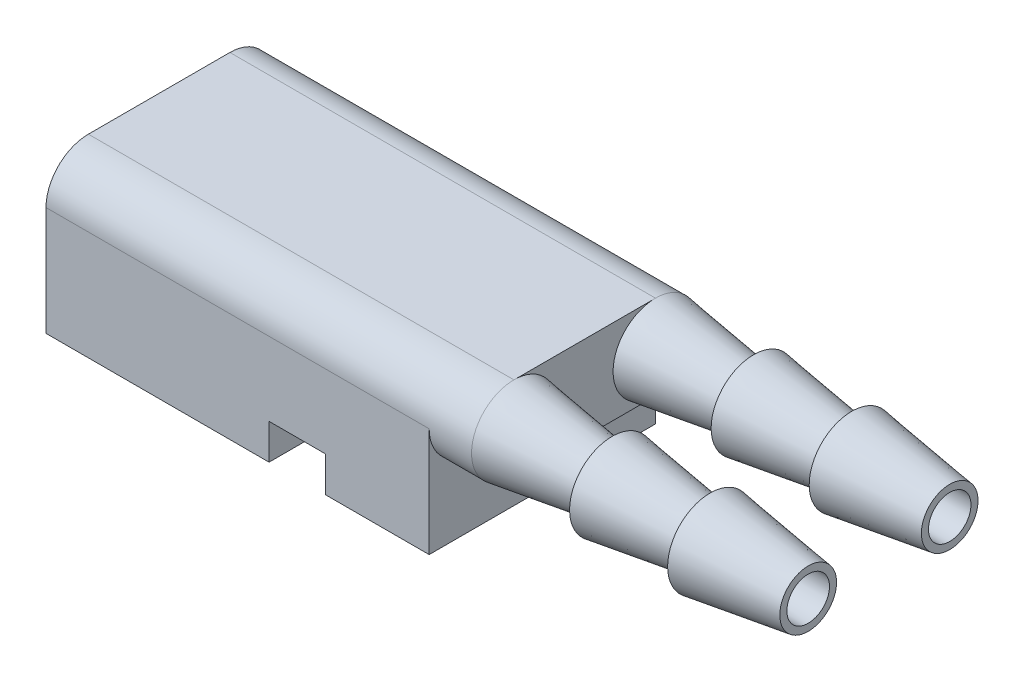
SolidWorks part; units mm, degrees
material "ABS"
ref_plane "Front Plane" through (0, 0, 0) normal (0, 0, 1) x (1, 0, 0)
ref_plane "Top Plane" through (0, 0, 0) normal (0, 1, 0) x (1, 0, 0)
ref_plane "Right Plane" through (0, 0, 0) normal (1, 0, 0) x (0, 0, -1)
sketch "Sketch1" plane through (0, 0, 0) normal (0, 1, 0) x (1, 0, 0)
  line L0 (0, 0) -> (95.5633, 0)
  line L1 (0, 3) -> (0, 1.5016)
  line L2 (0, 1.5016) -> (20.7853, 1.5016)
  line L3 (0, 3) -> (6.5856, 2.051)
  line L4 (6.9284, 2.3479) -> (6.9284, 3)
  line L5 (6.9284, 3) -> (13.5141, 2.051)
  line L6 (13.8569, 2.3479) -> (13.8569, 3)
  line L7 (13.8569, 3) -> (20.7853, 2.0016)
  line L8 (20.7853, 2.0016) -> (20.7853, 1.5016)
  line L9 (0, -8.4984) -> (20.7853, -8.4984)
  line L10 (0, -10) -> (26.2644, -10)
  line L11 (0, -7) -> (0, -8.4984)
  line L12 (0, -7) -> (6.5856, -7.949)
  line L13 (6.9284, -7.6521) -> (6.9284, -6.9984)
  line L14 (6.9284, -6.9984) -> (13.5141, -7.9474)
  line L15 (13.8569, -7.6505) -> (13.8569, -6.9968)
  line L16 (13.8569, -6.9968) -> (20.7853, -7.9952)
  line L17 (20.7853, -7.9952) -> (20.7853, -8.4984)
  arc A0 (13.8569, 2.3479) -> (13.5141, 2.051) centre (13.5569, 2.3479) cw
  arc A1 (6.9284, 2.3479) -> (6.5856, 2.051) centre (6.6284, 2.3479) cw
  arc A2 (13.8569, -7.6505) -> (13.5141, -7.9474) centre (13.5569, -7.6505) cw
  arc A3 (6.9284, -7.6521) -> (6.5856, -7.949) centre (6.6284, -7.6521) cw
  dimension "D1" = 0.3
  dimension "D2" = 0.3
revolve "Revolve1" add sketch "Sketch1" angle 360 about L0
sketch "Sketch2" plane through (0, 0, 0) normal (0, 1, 0) x (1, 0, 0)
  line L0 (0, -7) -> (6.5856, -7.949)
  line L1 (0, -10) -> (22.7091, -10)
  line L2 (0, -8.5) -> (0, -7)
  line L3 (6.9284, -7.6521) -> (6.9284, -6.9984)
  line L4 (6.9284, -6.9984) -> (13.5141, -7.9474)
  line L5 (13.8569, -7.6505) -> (13.8569, -6.9968)
  line L6 (13.8569, -6.9968) -> (20.7853, -7.9952)
  line L7 (20.7853, -7.9952) -> (20.7853, -8.4952)
  line L8 (20.7853, -8.4952) -> (0, -8.5)
  arc A0 (13.8569, -7.6505) -> (13.5141, -7.9474) centre (13.5569, -7.6505) cw
  arc A1 (6.9284, -7.6521) -> (6.5856, -7.949) centre (6.6284, -7.6521) cw
  dimension "D1" = 0.3
revolve "Revolve2" add sketch "Sketch2" angle 360 about L1
sketch "Sketch3" plane through (0, 0, 0) normal (1, 0, 0) x (0, 0, -1)
  line L0 (0, 0) -> (-10, 0) construction
  line L1 (0, -2.9937) -> (-10, -2.9937)
  line L2 (0, 2.9937) -> (-10, 2.9937)
  arc A0 (0, -2.9937) -> (0, 2.9937) centre (0, 0) ccw
  arc A1 (-10, 2.9937) -> (-10, -2.9937) centre (-10, 0) ccw
  circle A2 centre (0, 0) radius 1.5016
  circle A3 centre (-10, 0) radius 1.5
  point P4 (-5, 0)
extrude "Boss-Extrude1" add sketch "Sketch3" against normal blind 30.0707
ref_plane "Plane1" through (-23.5707, 0, 0) normal (1, 0, 0) x (0, 0, -1)
sketch "Sketch4" plane through (-23.5707, 0, 0) normal (1, 0, 0) x (0, 0, -1)
  line L0 (-10, 0) -> (0, 0) construction
  line L1 (-10, 1.5126) -> (0, 1.5126)
  line L2 (-10, -1.5126) -> (0, -1.5126)
  arc A0 (-10, 1.5126) -> (-10, -1.5126) centre (-10, 0) ccw
  arc A1 (0, -1.5126) -> (0, 1.5126) centre (0, 0) ccw
  point P4 (-5, 0)
extrude "Cut-Extrude2" cut sketch "Sketch4" along normal blind 23
ref_plane "Plane2" through (-30.0707, 0, 0) normal (1, 0, 0) x (0, 0, -1)
sketch "Sketch5" plane through (-30.0707, 0, 0) normal (1, 0, 0) x (0, 0, -1)
  line L0 (-10, 0) -> (0, 0) construction
  line L1 (-10, 2.9915) -> (0, 2.9915)
  line L2 (-10, -2.9915) -> (0, -2.9915)
  arc A0 (-10, 2.9915) -> (-10, -2.9915) centre (-10, 0) ccw
  arc A1 (0, -2.9915) -> (0, 2.9915) centre (0, 0) ccw
  point P4 (-5, 0)
extrude "Boss-Extrude3" add sketch "Sketch5" along normal blind 6.5
ref_plane "Plane3" through (0, -3, 0) normal (0, 1, 0) x (1, 0, 0)
sketch "Sketch7" plane through (0, -3, 0) normal (0, 1, 0) x (1, 0, 0)
  circle A0 centre (-18.0707, -5) radius 5
extrude "Cut-Extrude3" cut sketch "Sketch7" along normal blind 3
sketch "Sketch8" plane through (0, -3, 0) normal (0, 1, 0) x (1, 0, 0)
  line L0 (-30.0707, -5) -> (-30.0707, -12.9937)
  line L1 (-30.0707, -12.9937) -> (-3, -12.9937)
  line L2 (-3, -12.9937) -> (-3, 2.9937)
  line L3 (-3, 2.9937) -> (-30.0707, 2.9937)
  line L4 (-30.0707, 2.9937) -> (-30.0707, -5)
  circle A1 centre (-18.0707, -5) radius 5
extrude "Boss-Extrude6" add sketch "Sketch8" against normal blind 4.7 and the other way up to next contours L4 L0 L1 L2 L3 | A1
ref_plane "Plane4" through (0, -7.7, 0) normal (0, 1, 0) x (1, 0, 0)
sketch "Sketch10" plane through (0, -7.7, 0) normal (0, 1, 0) x (1, 0, 0)
  line L0 (-30.0707, -12.9937) -> (-14.3107, -12.9937)
  line L1 (-30.0707, -12.9937) -> (-3, -12.9937) construction
  line L2 (-14.3107, -12.9937) -> (-14.3107, 2.9937)
  line L3 (-3, 2.9937) -> (-30.0707, 2.9937) construction
  line L4 (-14.3107, 2.9937) -> (-10.3107, 2.9937)
  line L5 (-10.3107, 2.9937) -> (-10.3107, -12.9937)
  line L6 (-10.3107, -12.9937) -> (-14.3107, -12.9937)
  point P10 (0, 0)
  point P11 (0, 0)
extrude "Cut-Extrude5" cut sketch "Sketch10" along normal blind 2.5 contours L6 L5 L4 L2
